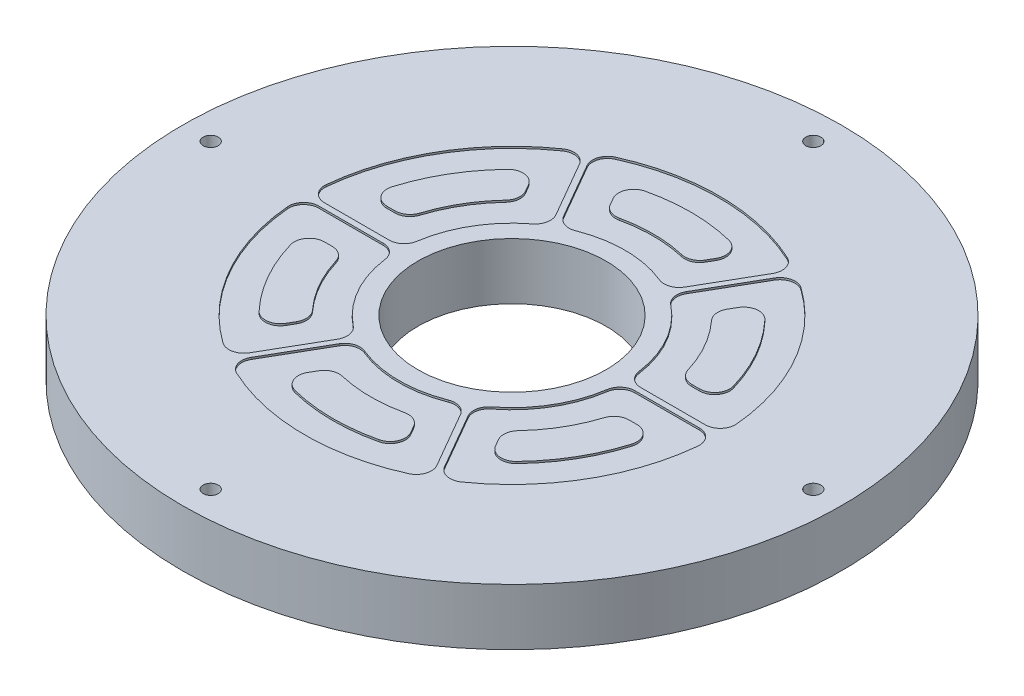
SolidWorks part; units mm, degrees
material "Oak"
ref_plane "Front Plane" through (0, 0, 0) normal (0, 0, 1) x (1, 0, 0)
ref_plane "Top Plane" through (0, 0, 0) normal (0, 1, 0) x (1, 0, 0)
ref_plane "Right Plane" through (0, 0, 0) normal (1, 0, 0) x (0, 0, -1)
sketch "Sketch2" plane through (0, 0, 0) normal (0, 1, 0) x (1, 0, 0)
  circle A0 centre (0, 0) radius 175
  dimension "D1" = 350
extrude "Boss-Extrude1" add sketch "Sketch2" along normal mid plane 30
sketch "Sketch3" plane through (0, 15, 0) normal (0, 1, 0) x (1, 0, 0)
  line L0 (0, -1000) -> (0, 49000) construction
  line L1 (-1000, 0) -> (49000, 0) construction
  circle A0 centre (0, 160) radius 4
  circle A1 centre (0, -160) radius 4
  circle A2 centre (-160, 0) radius 4
  circle A3 centre (160, 0) radius 4
  circle A4 centre (0, 0) radius 50
  point P7 (0, -160)
  dimension "D1" = 8
  dimension "D3" = 8
  dimension "D4" = 160
  dimension "D5" = 100
  dimension "D2" = 160
extrude "Cut-Extrude1" cut sketch "Sketch3" against normal blind 30
sketch "Sketch4" plane through (0, 15, 0) normal (0, 1, 0) x (1, 0, 0)
  line L0 (0, -1000) -> (0, 49000) construction
  line L1 (-1000, 0) -> (49000, 0) construction
  line L2 (0, 0) -> (45, 77.9423) construction
  line L3 (0, 0) -> (-45, -77.9423) construction
  line L4 (0, 0) -> (-45, 77.9423) construction
  line L5 (0, 0) -> (45, -77.9423) construction
  line L6 (-67.2607, 2) -> (-101.5086, 2)
  line L10 (-34.5669, 57.8717) -> (-51.6671, 87.4901)
  line L11 (-79.1454, 17) -> (-83.3307, 17)
  line L12 (-53.5836, 60.8095) -> (-55.6685, 64.4206)
  line L13 (-73.0479, 17) -> (-93.4666, 17) construction
  line L14 (-50.4931, 55.4567) -> (-60.6779, 73.0972) construction
  line L15 (-30.8619, 51.4543) -> (-55.8638, 94.7589) construction
  line L16 (-59.9667, 2) -> (-109.9818, 2) construction
  circle A0 centre (0, 0) radius 90 construction
  arc A7 (-63.191, 90.0383) -> (-109.4701, 10.7843) centre (0, 0) ccw
  arc A8 (-36.6133, 47.5338) -> (-59.3477, 8.8235) centre (0, 0) ccw
  arc A11 (-68.3527, 65.9766) -> (-90.9933, 27.2989) centre (0, 0) ccw
  arc A12 (-54.6793, 51.3339) -> (-71.517, 22.5904) centre (0, 0) ccw
  arc A13 (-60.6779, 73.0972) -> (-93.4666, 17) centre (0, 0) ccw construction
  arc A14 (-83.3307, 17) -> (-90.9933, 27.2989) centre (-83.3307, 25) cw
  arc A15 (-50.4931, 55.4567) -> (-73.0479, 17) centre (0, 0) ccw construction
  arc A16 (-79.1454, 17) -> (-71.517, 22.5904) centre (-79.1454, 25) ccw
  arc A17 (-53.5836, 60.8095) -> (-54.6793, 51.3339) centre (-60.5118, 56.8095) cw
  arc A18 (-55.6685, 64.4206) -> (-68.3527, 65.9766) centre (-62.5967, 60.4206) ccw
  arc A19 (-55.8638, 94.7589) -> (-109.9818, 2) centre (0, 0) ccw construction
  arc A20 (-51.6671, 87.4901) -> (-63.191, 90.0383) centre (-58.5953, 83.4901) ccw
  arc A21 (-109.4701, 10.7843) -> (-101.5086, 2) centre (-101.5086, 10) ccw
  arc A22 (-30.8619, 51.4543) -> (-59.9667, 2) centre (0, 0) ccw construction
  arc A23 (-59.3477, 8.8235) -> (-67.2607, 2) centre (-67.2607, 10) cw
  arc A24 (-36.6133, 47.5338) -> (-34.5669, 57.8717) centre (-41.4951, 53.8717) ccw
  point P15 (-90, 0)
  point P16 (90, 0)
  point P47 (0, 0)
  dimension "D1" = 180
  dimension "D2" = 60
  dimension "D4" = 60
  dimension "D5" = 110
  dimension "D6" = 2
  dimension "D7" = 2
  dimension "D8" = 15
  dimension "D9" = 8
  dimension "D11" = 64.7343
  dimension "D12" = 98.9582
  dimension "D10" = 20
  dimension "D3" = 60
extrude "Cut-Extrude3" cut sketch "Sketch4" against normal blind 1 contours A8 A24 L10 A20 A7 A21 L6 A23 A18 L12 A17 A12 A16 L11 A14 A11
pattern_circular "CirPattern2" count 6 over 360 about axis through (0, 0, 0) along (0, 1, 0) of "Cut-Extrude3"
